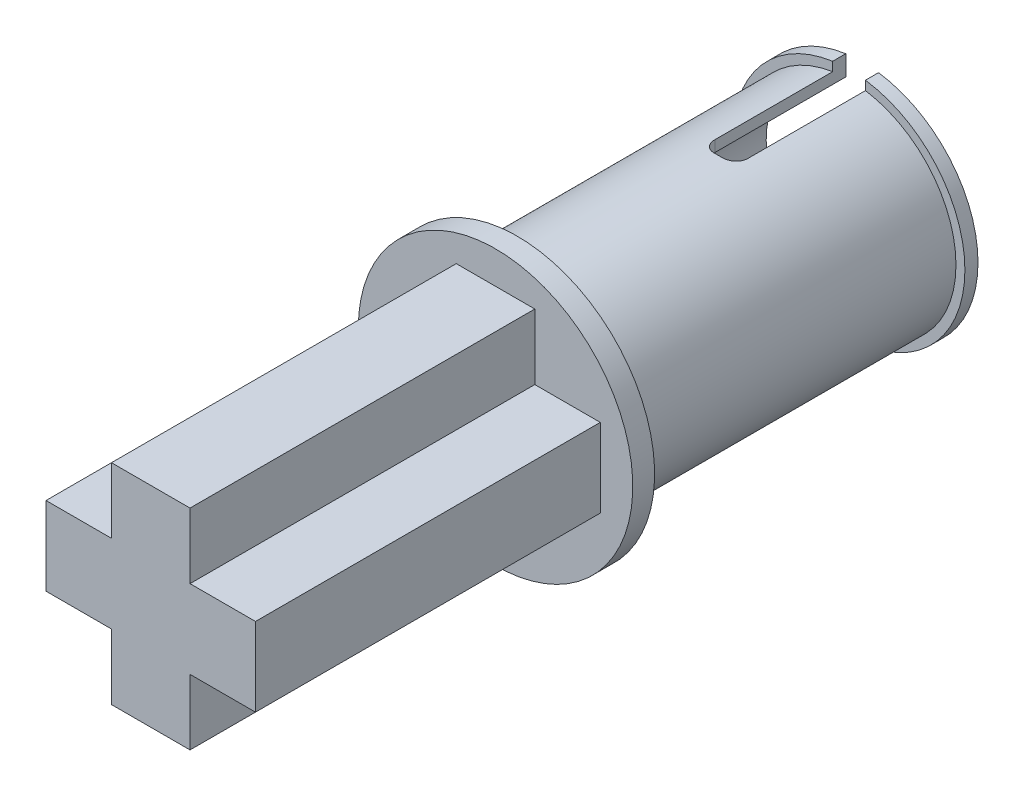
SolidWorks part; units mm, degrees
ref_plane "Front Plane" through (0, 0, 0) normal (0, 0, 1) x (1, 0, 0)
ref_plane "Top Plane" through (0, 0, 0) normal (0, 1, 0) x (1, 0, 0)
ref_plane "Right Plane" through (0, 0, 0) normal (1, 0, 0) x (0, 0, -1)
sketch "Sketch1" plane through (0, 0, 0) normal (0, 0, 1) x (1, 0, 0)
  line L0 (-2.4, 0) -> (2.4, 0)
  line L1 (-2.4, 0.9) -> (-2.4, -0.9)
  line L2 (-2.4, 0.9) -> (-0.9, 0.9)
  line L3 (0, 2.4) -> (0, -2.4)
  line L4 (-0.9, 0.9) -> (-0.9, 2.4)
  line L5 (-0.9, 2.4) -> (0.9, 2.4)
  line L6 (0.9, 0.9) -> (0.9, 2.4)
  line L7 (2.4, 0.9) -> (0.9, 0.9)
  line L8 (2.4, 0.9) -> (2.4, -0.9)
  line L9 (2.4, -0.9) -> (0.9, -0.9)
  line L10 (0.9, -0.9) -> (0.9, -2.4)
  line L11 (-0.9, -2.4) -> (0.9, -2.4)
  line L12 (-0.9, -0.9) -> (-0.9, -2.4)
  line L13 (-2.4, -0.9) -> (-0.9, -0.9)
  point P4 (0, 0)
  point P8 (-2.4, 0)
  point P12 (0, 0)
  dimension "D1" = 4.8
  dimension "D2" = 1.8
  dimension "D3" = 1.5
  dimension "D4" = 4.8
  dimension "D5" = 1.8
extrude "Boss-Extrude1" add sketch "Sketch1" along normal blind 7.9 contours L5 L4 L2 L1 L0 L3 | L1 L13 L12 L11 L3 L0 | L8 L7 L6 L5 L3 L0 | L3 L11 L10 L9 L8 L0
sketch "Sketch2" plane through (0, 0, 0) normal (0, 0, -1) x (-1, 0, 0)
  circle A0 centre (0, 0) radius 3.1445
extrude "Boss-Extrude3" add sketch "Sketch2" along normal blind 0.5 contours A0
sketch "Sketch3" plane through (0, 0, -0.5) normal (0, 0, -1) x (-1, 0, 0)
  circle A0 centre (0, 0) radius 2.45
  dimension "D1" = 4.9
extrude "Boss-Extrude4" add sketch "Sketch3" along normal blind 7.9
sketch "Sketch4" plane through (0, 0, -8.4) normal (0, 0, -1) x (-1, 0, 0)
  circle A0 centre (0, 0) radius 2.6546
extrude "Boss-Extrude5" add sketch "Sketch4" against normal blind 0.3
sketch "Sketch5" plane through (0, 0, -8.4) normal (0, 0, -1) x (-1, 0, 0)
  circle A0 centre (0, 0) radius 2.1986
extrude "Cut-Extrude1" cut sketch "Sketch5" against normal up to surface (7.9 mm away) up to face at (-2.45, 0, -0.5)
sketch "Sketch6" plane through (0, 0, -8.4) normal (0, 0, -1) x (-1, 0, 0)
  line L0 (0, 0) -> (2.6546, 0) construction
  line L1 (0, 0) -> (0, 2.6546) construction
  line L2 (0.3755, 2.6546) -> (0.3755, 2.1663)
  line L3 (0.3755, 2.6546) -> (-0.3755, 2.6546)
  line L4 (0, 2.6546) -> (0, 2.1663)
  line L5 (0.3755, 2.1663) -> (-0.3755, 2.1663)
  line L6 (-0.3755, 2.6546) -> (-0.3755, 2.1663)
  line L7 (0.3755, -2.6546) -> (0.3755, -2.1663)
  line L8 (0.3755, -2.6546) -> (-0.3755, -2.6546)
  line L9 (-0.3755, -2.6546) -> (-0.3755, -2.1663)
  line L10 (0.3755, -2.1663) -> (-0.3755, -2.1663)
  circle A0 centre (0, 0) radius 2.6546 construction
  circle A1 centre (0, 0) radius 2.1986 construction
  circle M8 centre (0, 0) radius 2.1986
  circle M9 centre (0, 0) radius 2.6546
extrude "Cut-Extrude2" cut sketch "Sketch6" against normal blind 3.3 contours L4 L2 M9 M8 | L6 L4 M9 M8 | L9 L7 M9 M8
fillet "Fillet1" radius 0.3 4 edges at (-0.3755, -2.2937, -5.1) (0.3755, -2.2937, -5.1) (-0.3755, 2.2937, -5.1) (0.3755, 2.2937, -5.1)
